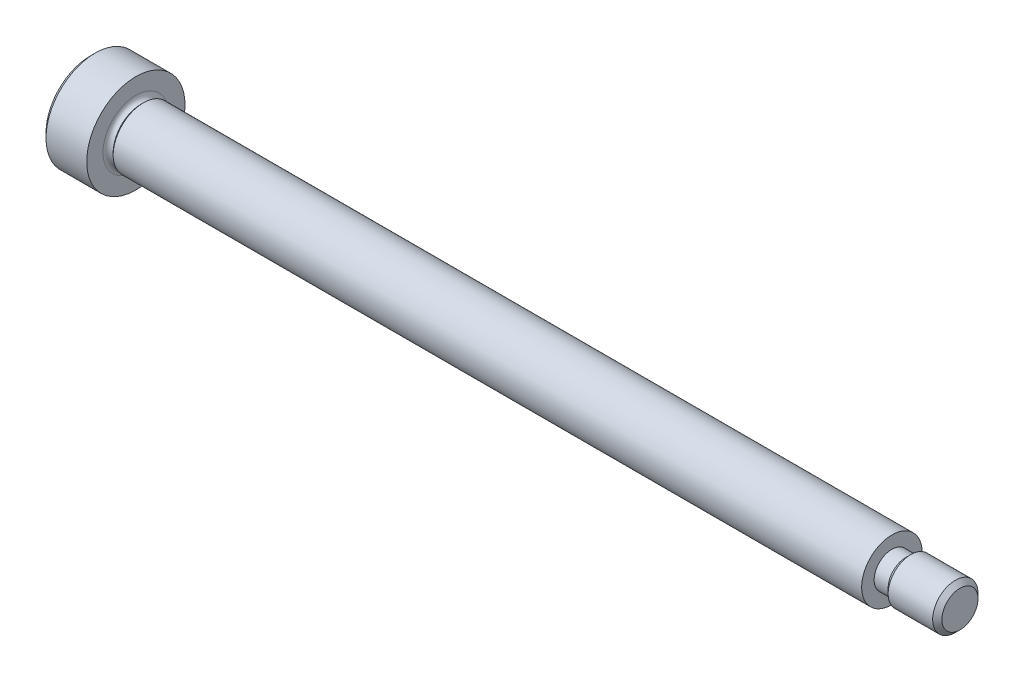
SolidWorks part; units mm, degrees
ref_plane "Front Plane" through (0, 0, 0) normal (0, 0, 1) x (1, 0, 0)
ref_plane "Top Plane" through (0, 0, 0) normal (0, 1, 0) x (1, 0, 0)
ref_plane "Right Plane" through (0, 0, 0) normal (1, 0, 0) x (0, 0, -1)
sketch "Sketch1" plane through (0, 0, 0) normal (0, 0, 1) x (1, 0, 0)
  line L0 (-6, 6.5) -> (-6, 0)
  line L1 (-6, 0) -> (100, 0)
  line L2 (100, 0) -> (100, 4)
  line L3 (100, 4) -> (1, 4)
  line L4 (1, 4) -> (0.7, 3.7)
  line L5 (0, 4.35) -> (0, 6.5)
  line L6 (0, 6.5) -> (-6, 6.5)
  line L7 (-6, 0) -> (100, 0) construction
  arc A0 (0.7, 3.7) -> (0, 4.35) centre (0.6306, 4.3272) cw
  dimension "D1" = 106
revolve "Revolve1" add sketch "Sketch1" angle 360 about L7
sketch "Sketch2" plane through (100, 0, 0) normal (1, 0, 0) x (0, 0, -1)
  circle A0 centre (0, 0) radius 2.35
extrude "Boss-Extrude1" add sketch "Sketch2" along normal blind 1.85
sketch "Sketch3" plane through (101.85, 0, 0) normal (1, 0, 0) x (0, 0, -1)
  circle A0 centre (0, 0) radius 2.35
extrude "Boss-Extrude2" add sketch "Sketch3" along normal blind 0.65 draft 45 draft outward yes
sketch "Sketch4" plane through (102.5, 0, 0) normal (1, 0, 0) x (0, 0, -1)
  circle A0 centre (0, 0) radius 3
extrude "Boss-Extrude3" add sketch "Sketch4" along normal blind 6.5
sketch "Sketch5" plane through (-6, 0, 0) normal (-1, 0, 0) x (0, 0, 1)
  line L0 (0, -2.8868) -> (2.5, -1.4434)
  line L1 (2.5, -1.4434) -> (2.5, 1.4434)
  line L2 (2.5, 1.4434) -> (0, 2.8868)
  line L3 (0, 2.8868) -> (-2.5, 1.4434)
  line L4 (-2.5, 1.4434) -> (-2.5, -1.4434)
  line L5 (-2.5, -1.4434) -> (0, -2.8868)
extrude "Cut-Extrude1" cut sketch "Sketch5" against normal blind 3
sketch "Sketch6" plane through (0, 0, 0) normal (0, 0, 1) x (1, 0, 0)
  line L0 (-3, 2.5) -> (-3, 0)
  line L1 (-3, 0) -> (-1.5566, 0)
  line L2 (-1.5566, 0) -> (-3, 2.5)
  line L3 (-3, 0) -> (-1.5566, 0) construction
revolve "Cut-Revolve1" cut sketch "Sketch6" angle 360 about L3
chamfer "Chamfer1" distance 0.6135 angle 45 2 edges at (-6, 0, -6.5) (109, 0, -3)
